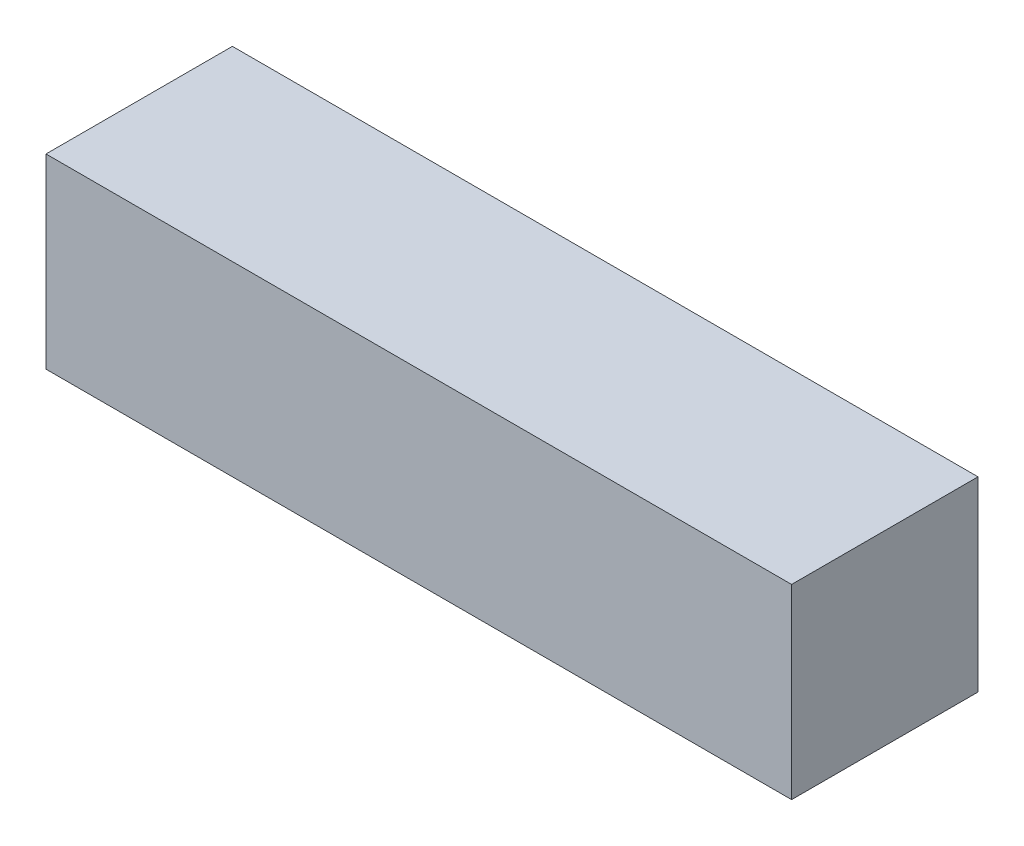
SolidWorks part; units mm, degrees
ref_plane "Front Plane" through (0, 0, 0) normal (0, 0, 1) x (1, 0, 0)
ref_plane "Top Plane" through (0, 0, 0) normal (0, 1, 0) x (1, 0, 0)
ref_plane "Right Plane" through (0, 0, 0) normal (1, 0, 0) x (0, 0, -1)
sketch "Sketch1" plane through (0, 0, 0) normal (0, 0, 1) x (1, 0, 0)
  line L1 (0, 0) -> (140, 0)
  line L2 (0, 0) -> (0, 35)
  line L3 (0, 35) -> (140, 35)
  line L4 (140, 0) -> (140, 35)
  dimension "D1" = 140
  dimension "D2" = 35
extrude "Boss-Extrude1" add sketch "Sketch1" along normal blind 35
